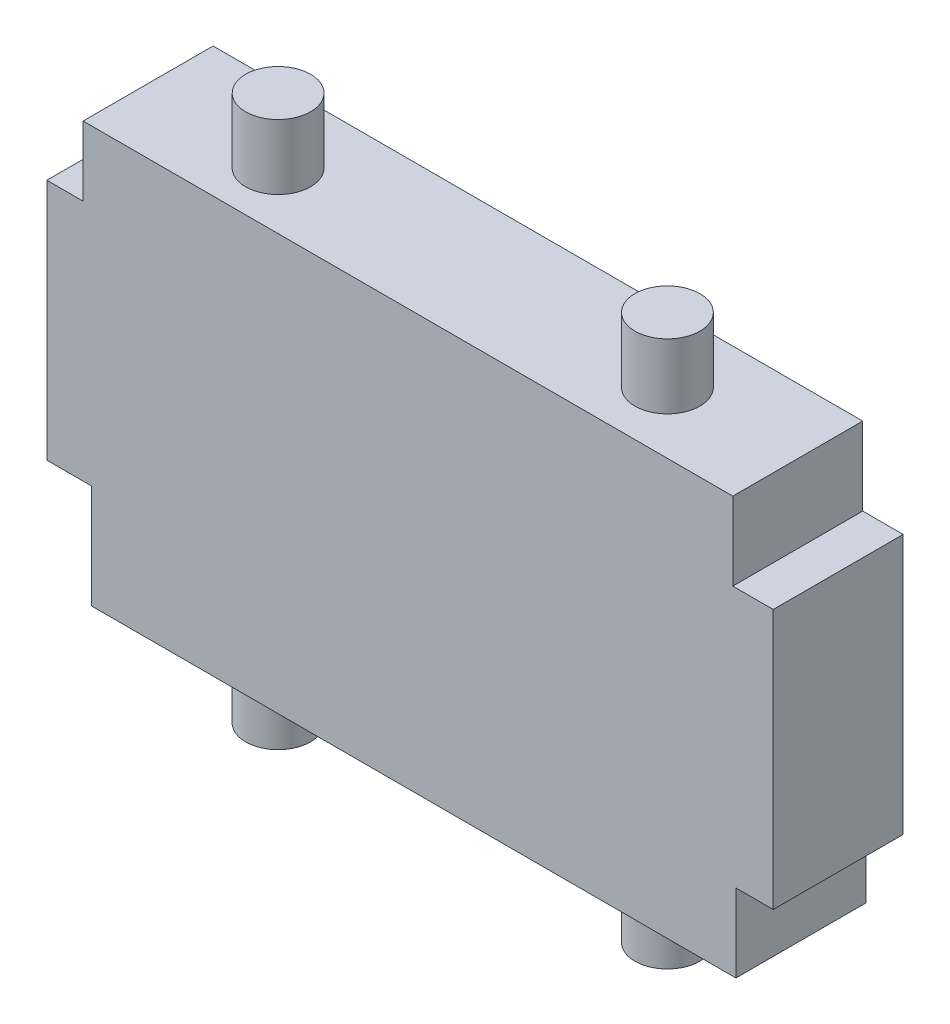
SolidWorks part; units mm, degrees
ref_plane "Front Plane" through (0, 0, 0) normal (0, 0, 1) x (1, 0, 0)
ref_plane "Top Plane" through (0, 0, 0) normal (0, 1, 0) x (1, 0, 0)
ref_plane "Right Plane" through (0, 0, 0) normal (1, 0, 0) x (0, 0, -1)
sketch "Sketch1" plane through (0, 0, 0) normal (0, 0, 1) x (1, 0, 0)
  line L0 (-77.1722, 33.9274) -> (49.8278, 33.9274)
  line L1 (49.8278, 33.9274) -> (49.8278, 18.6874)
  line L2 (49.8278, 18.6874) -> (57.7273, 18.6874)
  line L3 (57.7273, 18.6874) -> (57.7273, -32.1126)
  line L4 (57.7273, -32.1126) -> (50.4354, -32.1126)
  line L6 (50.4354, -32.1126) -> (57.7273, -32.1126)
  line L7 (50.4354, -47.3526) -> (50.4354, -32.1126)
  line L8 (-75.5518, -47.3526) -> (50.4354, -47.3526)
  line L10 (-75.5518, -47.3526) -> (-75.5518, -27.0407)
  line L11 (-84.2616, -27.0407) -> (-75.5518, -27.0407)
  line L12 (-84.2616, 20.3565) -> (-84.2616, -27.0407)
  line L13 (-77.1722, 20.3565) -> (-84.2616, 20.3565)
  line L14 (-77.1722, 33.9274) -> (-77.1722, 20.3565)
  dimension "D1" = 127
  dimension "D2" = 15.24
  dimension "D3" = 15.24
  dimension "D4" = 50.8
extrude "Boss-Extrude1" add sketch "Sketch1" along normal blind 25.4 contours L0 L14 L13 L12 L11 L10 L8 L7 L4 L3 L2 L1
sketch "Sketch2" plane through (0, -47.3526, 0) normal (0, -1, 0) x (1, 0, 0)
  line L3 (-75.5518, 25.4) -> (-75.5518, 0) construction
  line L4 (50.4354, 25.4) -> (50.4354, 0) construction
  circle A0 centre (-50.1518, 14.3066) radius 6.35
  circle A1 centre (25.0354, 13.3885) radius 6.35
  dimension "D1" = 12.7
  dimension "D2" = 12.7
  dimension "D3" = 25.4
  dimension "D4" = 25.4
sketch "Sketch3" plane through (0, 0, 25.4) normal (0, 0, 1) x (1, 0, 0)
  line L0 (-84.2616, -3.3421) -> (57.7273, -3.3421) construction
  line L1 (-84.2616, 20.3565) -> (-84.2616, -27.0407) construction
  line L2 (57.7273, 18.6874) -> (57.7273, -32.1126) construction
sketch "Sketch4" plane through (0, 33.9274, 0) normal (0, 1, 0) x (1, 0, 0)
  circle A0 centre (-50.1518, -14.3066) radius 6.35
  circle A1 centre (25.0354, -13.3885) radius 6.35
extrude "Boss-Extrude2" add sketch "Sketch4" along normal blind 12.7
extrude "Boss-Extrude3" add sketch "Sketch2" along normal blind 12.7
sketch "Sketch5" plane through (0, 33.9274, 0) normal (0, 1, 0) x (1, 0, 0)
  circle A0 centre (-50.1518, -14.3066) radius 21.59
  circle A1 centre (25.0354, -13.3885) radius 21.59
  dimension "D1" = 43.18
  dimension "D2" = 43.18
